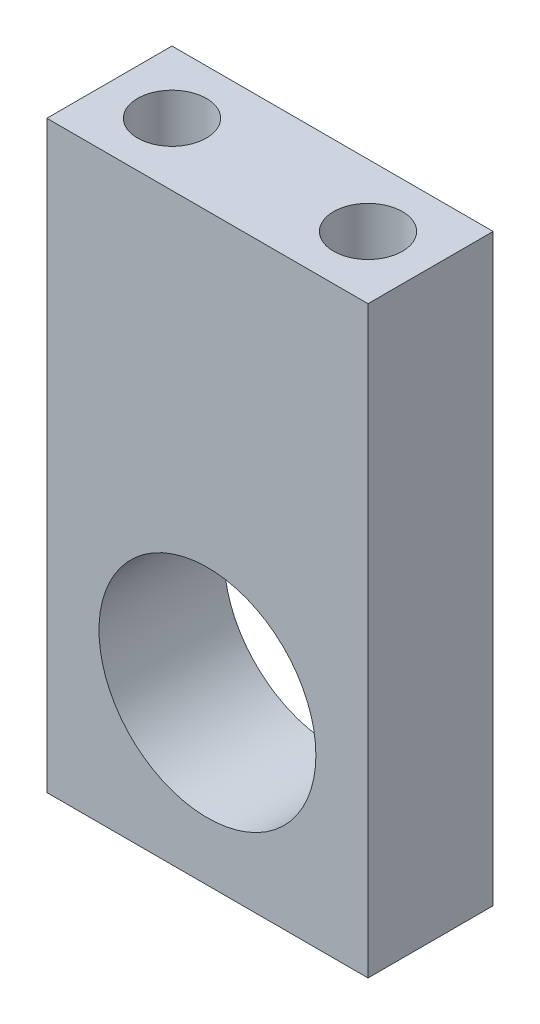
SolidWorks part; units mm, degrees
ref_plane "Front" through (0, 0, 0) normal (0, 0, 1) x (1, 0, 0)
ref_plane "Top" through (0, 0, 0) normal (0, 1, 0) x (1, 0, 0)
ref_plane "Right" through (0, 0, 0) normal (1, 0, 0) x (0, 0, -1)
sketch "Sketch1" plane through (0, 0, 0) normal (0, 1, 0) x (1, 0, 0)
  line L1 (-7.7, 3) -> (7.7, 3)
  line L2 (-7.7, 3) -> (-7.7, -3)
  line L3 (-7.7, -3) -> (7.7, -3)
  line L4 (7.7, 3) -> (7.7, -3)
  line L5 (-7.7, 3) -> (7.7, -3) construction
  line L6 (-7.7, -3) -> (7.7, 3) construction
  point P1 (0, 0)
  dimension "D1" = 6
  dimension "D2" = 15.4
extrude "Boss-Extrude1" add sketch "Sketch1" along normal blind 28
sketch "Sketch Reference for holes" plane through (0, 28, 0) normal (0, 1, 0) x (1, 0, 0)
  line L0 (0, 3) -> (0, -3) construction
  line L2 (-7.7, -3) -> (7.7, -3) construction
  line L7 (0, 0) -> (4.7, 0) construction
  line L8 (-4.7, 0) -> (0, 0) construction
  point P7 (0, 0)
  point P12 (0, 3)
  dimension "D1" = 4.7
hole_wizard "Tap Drill for M4x0.7 Tap1" positions "3DSketch1" profile "Sketch3" hole size "M4x0.7" standard "ANSI Metric"
sketch3d "3DSketch1"
  point P0 (-4.7, 28, 0)
  point P3 (4.7, 28, 0)
sketch "Sketch3" plane through (-4.7, 28, 0) normal (1, 0, 0) x (0, 0, 1)
  line L0 (0, 0) -> (0, 14.3914)
  line L1 (0, 14.3914) -> (1.65, 13.4)
  line L2 (1.65, 13.4) -> (1.65, 0)
  line L5 (1.65, 0) -> (0, 0)
  line L10 (0, 14.3914) -> (-1.65, 13.4) construction
  line L11 (0, -6.35) -> (0, 107.95) construction
  dimension "Hole Dia." = 3.3
  dimension "Hole Depth" = 13.4
  dimension "Drill Angle" = 118
sketch "Sketch4" plane through (0, 0, 3) normal (0, 0, 1) x (1, 0, 0)
  line L0 (0, 28) -> (0, 8) construction
  line L1 (-7.7, 28) -> (7.7, 28) construction
  circle A0 centre (0, 8) radius 5.2
  dimension "D2" = 10.4
  dimension "D1" = 20
extrude "Cut-Extrude Press Fit hole for solenoid tube" cut sketch "Sketch4" against normal up to next
